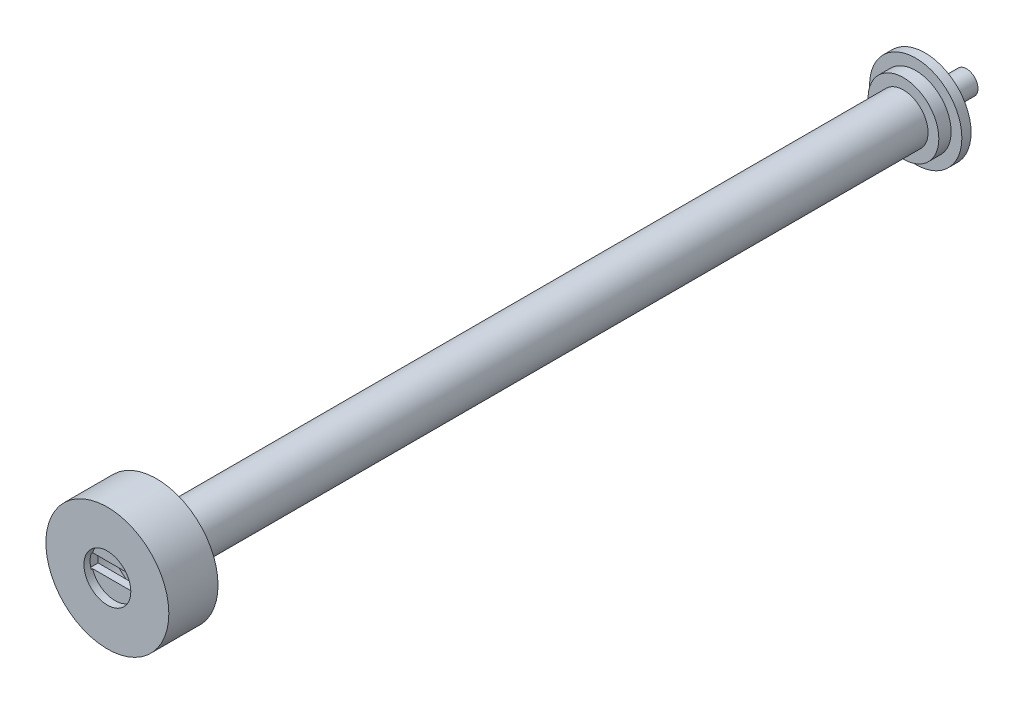
SolidWorks part; units mm, degrees
ref_plane "Front Plane" through (0, 0, 0) normal (0, 0, 1) x (1, 0, 0)
ref_plane "Top Plane" through (0, 0, 0) normal (0, 1, 0) x (1, 0, 0)
ref_plane "Right Plane" through (0, 0, 0) normal (1, 0, 0) x (0, 0, -1)
ref_plane "Plane_Z+54.60" through (0, 0, 54.6) normal (0, 0, 1) x (1, 0, 0)
sketch "Sketch1" plane through (0, 0, 54.6) normal (0, 0, 1) x (1, 0, 0)
  circle A0 centre (172, 45) radius 1.5
extrude "Socket_pin" add sketch "Sketch1" along normal blind 5.5
ref_plane "Plane_Z+60.00" through (0, 0, 60) normal (0, 0, 1) x (1, 0, 0)
sketch "Sketch2" plane through (0, 0, 60) normal (0, 0, 1) x (1, 0, 0)
  circle A0 centre (172, 45) radius 6
extrude "Mast_flange" add sketch "Sketch2" along normal blind 1.2
ref_plane "Plane_Z+61.20" through (0, 0, 61.2) normal (0, 0, 1) x (1, 0, 0)
sketch "Sketch3" plane through (0, 0, 61.2) normal (0, 0, 1) x (1, 0, 0)
  circle A0 centre (172, 45) radius 4.6
extrude "Mast_flange_step" add sketch "Sketch3" along normal blind 1.6
ref_plane "Plane_Z+62.70" through (0, 0, 62.7) normal (0, 0, 1) x (1, 0, 0)
sketch "Sketch4" plane through (0, 0, 62.7) normal (0, 0, 1) x (1, 0, 0)
  circle A0 centre (172, 45) radius 3.2
  dimension "MastTubeR" = 6.4
extrude "Mast_tube" add sketch "Sketch4" along normal blind 97.8
ref_plane "Plane_Z+160.00" through (0, 0, 160) normal (0, 0, 1) x (1, 0, 0)
sketch "Sketch5" plane through (0, 0, 160) normal (0, 0, 1) x (1, 0, 0)
  circle A0 centre (172, 45) radius 8
extrude "Beacon_base" add sketch "Sketch5" along normal blind 6.4
ref_plane "Plane_Z+162.60" through (0, 0, 162.6) normal (0, 0, 1) x (1, 0, 0)
sketch "Sketch6" plane through (0, 0, 162.6) normal (0, 0, 1) x (1, 0, 0)
  circle A0 centre (172, 45) radius 5.5
extrude "Solder_chamber" cut sketch "Sketch6" against normal mid plane 3.6
ref_plane "Plane_Z+164.90" through (0, 0, 164.9) normal (0, 0, 1) x (1, 0, 0)
sketch "Sketch7" plane through (0, 0, 164.9) normal (0, 0, 1) x (1, 0, 0)
  line L0 (168.8, 44.1) -> (175.2, 44.1)
  line L1 (175.2, 44.1) -> (175.2, 45.9)
  line L2 (175.2, 45.9) -> (168.8, 45.9)
  line L3 (168.8, 45.9) -> (168.8, 44.1)
extrude "LED_leg_slot" cut sketch "Sketch7" against normal mid plane 1.4
ref_plane "Plane_Z+166.10" through (0, 0, 166.1) normal (0, 0, 1) x (1, 0, 0)
sketch "Sketch8" plane through (0, 0, 166.1) normal (0, 0, 1) x (1, 0, 0)
  circle A0 centre (172, 45) radius 3.05
  dimension "LedFlangeSeat" = 6.1
extrude "LED_flange_counterbore" cut sketch "Sketch8" against normal mid plane 1.4
ref_plane "Plane_Z+112.00" through (0, 0, 112) normal (0, 0, 1) x (1, 0, 0)
sketch "Sketch9" plane through (0, 0, 112) normal (0, 0, 1) x (1, 0, 0)
  circle A0 centre (172, 45) radius 1.1
extrude "Wire_channel" cut sketch "Sketch9" against normal mid plane 98
ref_plane "Plane_Y+42.75" through (0, 42.75, 0) normal (0, 1, 0) x (1, 0, 0)
sketch "Sketch10" plane through (0, 42.75, 0) normal (0, 1, 0) x (1, 0, 0)
  circle A0 centre (172, -65) radius 1.1
extrude "Wire_exit" cut sketch "Sketch10" against normal mid plane 4.5
